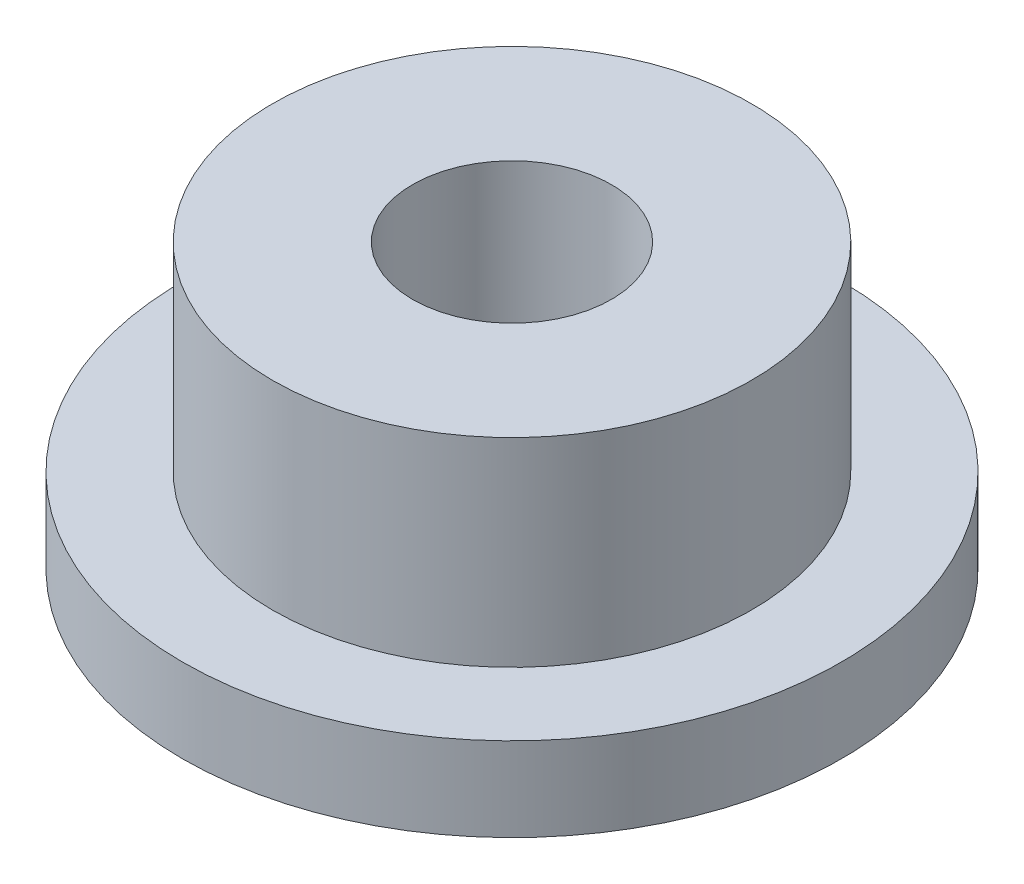
SolidWorks part; units mm, degrees
ref_plane "Front Plane" through (0, 0, 0) normal (0, 0, 1) x (1, 0, 0)
ref_plane "Top Plane" through (0, 0, 0) normal (0, 1, 0) x (1, 0, 0)
ref_plane "Right Plane" through (0, 0, 0) normal (1, 0, 0) x (0, 0, -1)
ref_plane "Plane1" through (0, 0, 0) normal (0, 0, -1) x (-1, 0, 0)
sketch "Sketch5" plane through (0, 0, 0) normal (0, 0, -1) x (-1, 0, 0)
  line L0 (-21.0344, 1) -> (-8.5, 1)
  line L1 (-8.5, 1) -> (-8.5, 0)
  line L2 (-8.5, 0) -> (-6.35, 0)
  line L3 (-6.35, 0) -> (-6.35, 19.05)
  line L4 (-6.35, 19.05) -> (-15.2908, 19.05)
  line L5 (-15.2908, 19.05) -> (-15.2908, 6.35)
  line L6 (-15.2908, 6.35) -> (-21.0344, 6.35)
  line L7 (-21.0344, 6.35) -> (-21.0344, 1)
  line L8 (0, 0) -> (0, 19.05) construction
revolve "Revolve2" add sketch "Sketch5" angle 360 about L8
sketch "Sketch7" plane through (0, 0, 0) normal (0, 0, 1) x (1, 0, 0)
  line L0 (6.35, 0) -> (0, 0)
  line L1 (0, 0) -> (0, -6.35)
  line L2 (0, -6.35) -> (6.35, -6.35)
  line L3 (6.35, -6.35) -> (6.35, 0)
  line L4 (0, 0) -> (0, -6.35) construction
revolve "Revolve3" add sketch "Sketch7" angle 360 about L1
